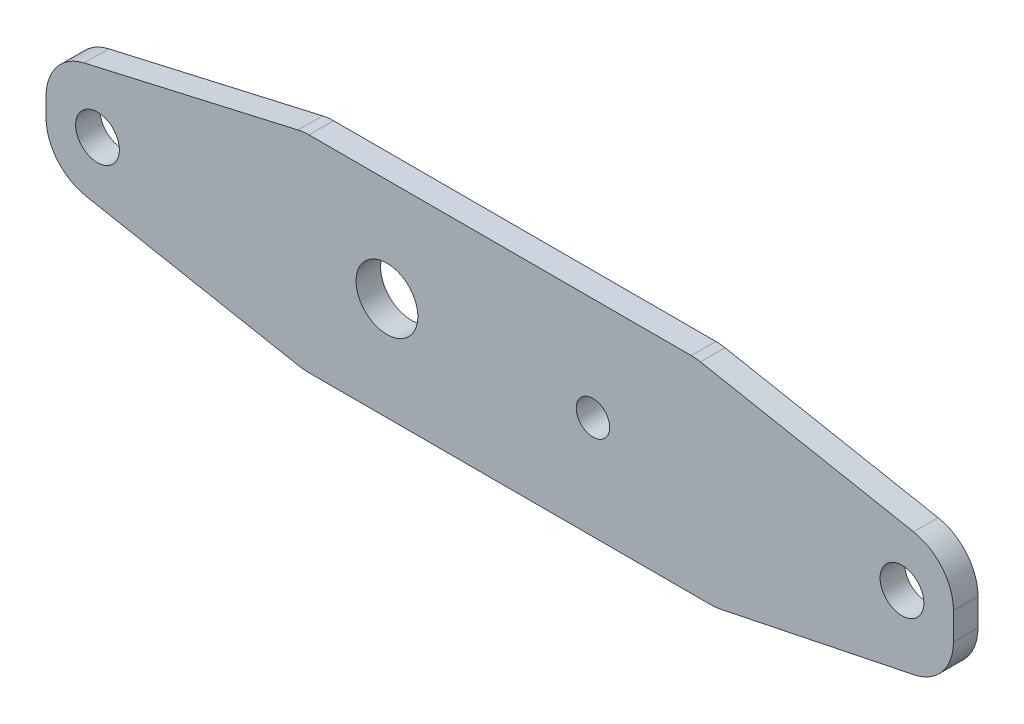
SolidWorks part; units mm, degrees
ref_plane "Front Plane" through (0, 0, 0) normal (0, 0, 1) x (1, 0, 0)
ref_plane "Top Plane" through (0, 0, 0) normal (0, 1, 0) x (1, 0, 0)
ref_plane "Right Plane" through (0, 0, 0) normal (1, 0, 0) x (0, 0, -1)
sketch "Sketch1" plane through (0, 0, 0) normal (0, 0, 1) x (1, 0, 0)
  line L0 (-45.4447, 407.1847) -> (-95.4447, 395.7597)
  line L1 (-45.4447, 367.1847) -> (34.5553, 367.1847)
  line L2 (-95.4447, 395.7597) -> (-95.4447, 376.7097)
  line L3 (-45.4447, 407.1847) -> (30.7553, 407.1847)
  line L5 (-95.4447, 376.7097) -> (-45.4447, 367.1847)
  line L6 (30.7553, 407.1847) -> (80.7553, 397.6547)
  line L7 (80.7553, 397.6547) -> (80.7553, 376.7147)
  line L8 (80.7553, 376.7147) -> (34.5553, 367.1847)
  circle A0 centre (-29.2447, 387.1847) radius 6
  circle A1 centre (10.7553, 387.1847) radius 3.25
  circle A2 centre (-85.4447, 386.2347) radius 4.25
  circle A3 centre (70.7553, 388.1347) radius 4.25
  dimension "D3" = 8.5
  dimension "D9" = 10
  dimension "D14" = 10
  dimension "D6" = 8.5
  dimension "D7" = 6.5
  dimension "D1" = 80
  dimension "D2" = 40
  dimension "D4" = 50
  dimension "D5" = 50
  dimension "D8" = 20
  dimension "D10" = 40
  dimension "D11" = 9.53
  dimension "D12" = 9.53
  dimension "D13" = 50
  dimension "D15" = 20
  dimension "D16" = 20
extrude "Boss-Extrude2" add sketch "Sketch1" along normal blind 4.7625
fillet "Fillet1" radius 9.53 8 edges at (-45.4447, 367.1847, 2.3813) (34.5553, 367.1847, 2.3813) (-45.4447, 407.1847, 2.3813) (30.7553, 407.1847, 2.3813) (80.7553, 376.7147, 2.3813) (80.7553, 397.6547, 2.3813) (-95.4447, 376.7097, 2.3813) (-95.4447, 395.7597, 2.3813)
